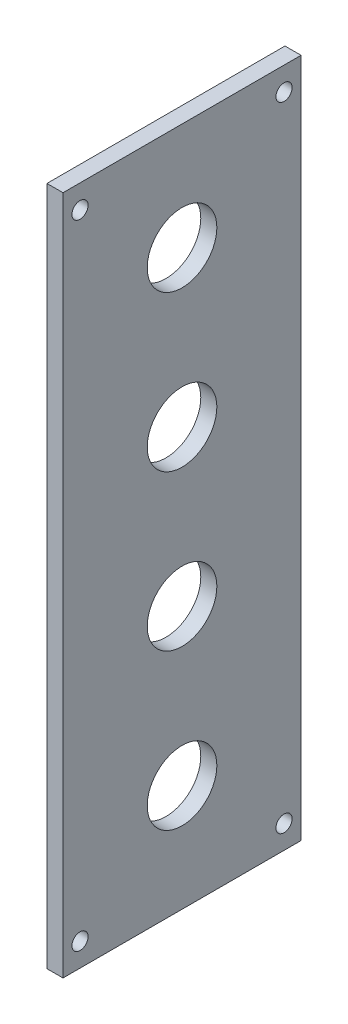
SolidWorks part; units mm, degrees
ref_plane "Front Plane" through (0, 0, 0) normal (1, 0, 0) x (0, 1, 0)
ref_plane "Top Plane" through (0, 0, 0) normal (0, 0, 1) x (0, 1, 0)
ref_plane "Right Plane" through (0, 0, 0) normal (0, 1, 0) x (-1, 0, 0)
sketch "Sketch1" plane through (0, 0, 0) normal (1, 0, 0) x (0, 1, 0)
  line L0 (0, -55) -> (0, 55) construction
  line L1 (-127, -44.45) -> (127, -44.45)
  line L2 (-127, -44.45) -> (-127, 44.45)
  line L3 (-127, 44.45) -> (127, 44.45)
  line L4 (127, -44.45) -> (127, 44.45)
  line L5 (-127, -44.45) -> (127, 44.45) construction
  line L6 (-127, 44.45) -> (127, -44.45) construction
  point P0 (0, 0)
  point P6 (-118.2625, -38.1)
  point P7 (-118.2625, -22.225)
  point P8 (-118.2625, -6.35)
  point P11 (-118.2625, 6.35)
  point P12 (-118.2625, 22.225)
  point P13 (-118.2625, 38.1)
  point P14 (118.2625, -38.1)
  point P15 (118.2625, -22.225)
  point P16 (118.2625, -6.35)
  point P17 (118.2625, 6.35)
  point P18 (118.2625, 22.225)
  point P19 (118.2625, 38.1)
  dimension "D1" = 254
  dimension "D2" = 88.9
  dimension "D3" = 118.2625
  dimension "D4" = 6.35
  dimension "D5" = 3
  dimension "D6" = 2
extrude "Boss-Extrude1" add sketch "Sketch1" against normal blind 6
sketch "Sketch2" plane through (0, 0, 0) normal (1, 0, 0) x (0, 1, 0)
  line L0 (-127, -44.45) -> (127, -44.45) construction
  line L1 (0, -3.3) -> (0, 3.3) construction
  point P5 (-118.2625, 38.1)
  point P6 (-118.2625, -38.1)
  point P9 (118.2625, -38.1)
  point P17 (118.2625, 38.1)
  dimension "D1" = 6.35
  dimension "D2" = 118.2625
hole_wizard "#10 Clearance Hole1" positions "Sketch2" profile "Sketch3" hole size "#10" standard "ANSI Inch" end condition up to next
sketch "Sketch3" plane through (0, 118.2625, 38.1) normal (0, 1, 0) x (0, 0, -1)
  line L0 (0, 0) -> (0, 6)
  line L1 (0, 6) -> (3.0226, 6)
  line L2 (3.0226, 6) -> (3.0226, 0)
  line L5 (3.0226, 0) -> (0, 0)
  line L11 (0, -6.35) -> (0, 107.95) construction
  dimension "Thru Hole Dia." = 6.0452
  dimension "Thru Hole Depth" = 6
hole_wizard "M22 Clearance Hole1" positions "Sketch4" profile "Sketch5" hole size "M22" standard "ANSI Metric" end condition through all
sketch "Sketch4" plane through (0, 0, 0) normal (1, 0, 0) x (0, 1, 0)
  line L0 (127, -44.45) -> (127, 44.45) construction
  line L1 (-127, 44.45) -> (-127, -44.45) construction
  point P0 (87, 0)
  point P15 (29, 0)
  point P16 (-29, 0)
  point P17 (-87, 0)
  dimension "D1" = 40
  dimension "D2" = 0
  dimension "D4" = 40
  dimension "D3" = 4
sketch "Sketch5" plane through (0, 87, 0) normal (0, 1, 0) x (0, 0, -1)
  line L0 (0, 0) -> (0, 6)
  line L1 (0, 6) -> (13, 6)
  line L2 (13, 6) -> (13, 0)
  line L5 (13, 0) -> (0, 0)
  line L11 (0, -6.35) -> (0, 107.95) construction
  dimension "Thru Hole Dia." = 26
  dimension "Thru Hole Depth" = 6
equation "\"size\"= 2"
equation "\"height\"= 44.45 * \"size\""
equation "\"D2@Sketch1\"=\"height\""
